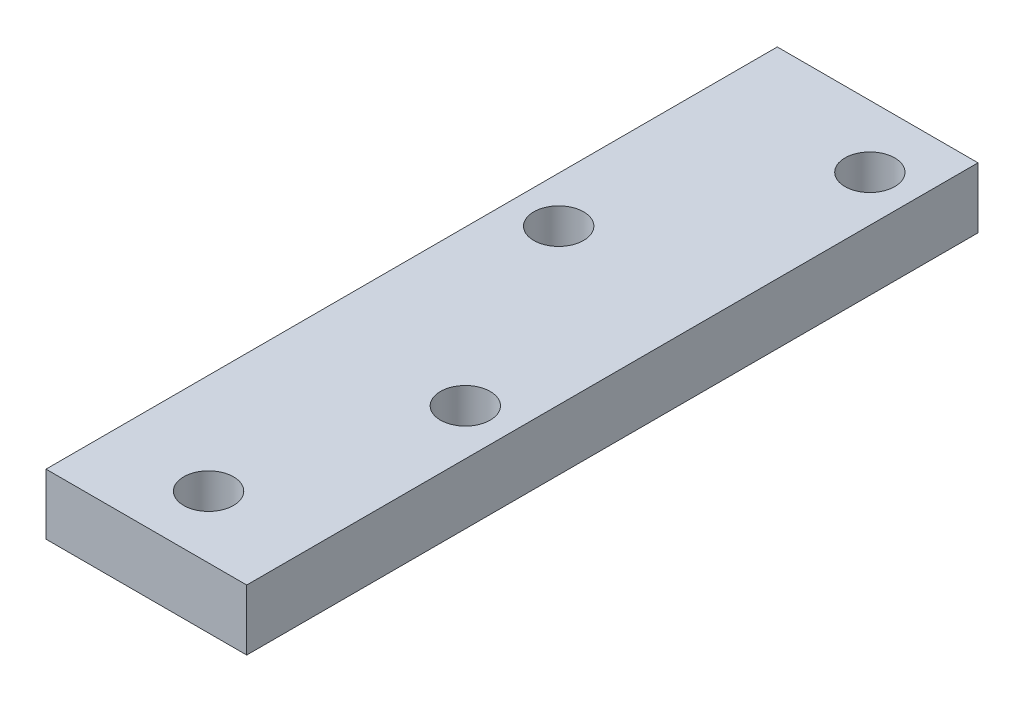
SolidWorks part; units mm, degrees
material "PLA"
ref_plane "前视基准面" through (0, 0, 0) normal (0, 0, 1) x (1, 0, 0)
ref_plane "上视基准面" through (0, 0, 0) normal (0, 1, 0) x (1, 0, 0)
ref_plane "右视基准面" through (0, 0, 0) normal (1, 0, 0) x (0, 0, -1)
sketch "草图1" plane through (0, 0, 0) normal (0, 0, 1) x (1, 0, 0)
  line L0 (0, 3) -> (0, -3)
  line L1 (7.5, -3) -> (0, -3)
  line L2 (7.5, -3) -> (7.5, 3)
  line L3 (7.5, 3) -> (0, 3)
  line L4 (-7.5, -3) -> (-7.5, 3) construction
  line L5 (7.5, -3) -> (-7.5, 3) construction
  line L6 (7.5, 3) -> (-7.5, -3) construction
  point P0 (0, 0)
  dimension "D1" = 15
  dimension "D2" = 6
extrude "凸台-拉伸1" add sketch "草图1" along normal blind 2
sketch "草图2" plane through (0, 0, 2) normal (0, 0, 1) x (1, 0, 0)
  line L1 (6.45, -1.95) -> (-6.45, -1.95)
  line L2 (6.45, -1.95) -> (6.45, 1.95)
  line L3 (6.45, 1.95) -> (-6.45, 1.95)
  line L4 (-6.45, -1.95) -> (-6.45, 1.95)
  line L5 (6.45, -1.95) -> (-6.45, 1.95) construction
  line L6 (6.45, 1.95) -> (-6.45, -1.95) construction
  point P0 (0, 0)
  dimension "D1" = 12.9
  dimension "D2" = 3.9
extrude "凸台-拉伸2" add sketch "草图2" along normal blind 52
sketch "草图3" plane through (0, -1.95, 0) normal (0, -1, 0) x (1, 0, 0)
  line L0 (3.5, 2) -> (3.5, 37) construction
  line L1 (0, 2) -> (6.45, 2) construction
  line L2 (7.5, 24.6481) -> (7.5, 6.8705) construction
  line L3 (-7.5, 24.6481) -> (-7.5, 6.3884) construction
  line L4 (0, 2) -> (7.5, 2) construction
  circle A0 centre (3.5, 37) radius 1.6
  circle A1 centre (3.5, 11) radius 1.6
  circle A2 centre (-3.5, 24) radius 1.6
  circle A3 centre (0, 50) radius 1.6
  dimension "D1" = 3.2
  dimension "D2" = 7.5
  dimension "D3" = 7.5
  dimension "D4" = 4
  dimension "D5" = 8
  dimension "D6" = 9
  dimension "D7" = 26
  dimension "D8" = 13
  dimension "D9" = 13
  dimension "D10" = 3.5
extrude "切除-拉伸1" cut sketch "草图3" against normal blind 356
sketch "草图4" plane through (0, 0, 2) normal (0, 0, 1) x (1, 0, 0)
  line L0 (0, 1.95) -> (7.5, 1.95)
  line L1 (7.5, -3) -> (7.5, 3) construction
  line L2 (7.5, 1.95) -> (7.5, 3)
  line L3 (7.5, 3) -> (0, 3)
  line L4 (0, 3) -> (0, 1.95)
extrude "切除-拉伸2" cut sketch "草图4" against normal blind 10
sketch "草图5" plane through (0, 1.95, 0) normal (0, 1, 0) x (1, 0, 0)
  line L1 (-11.1428, 16.1475) -> (11.1428, 16.1475)
  line L2 (-11.1428, 16.1475) -> (-11.1428, -7)
  line L3 (-11.1428, -7) -> (11.1428, -7)
  line L4 (11.1428, 16.1475) -> (11.1428, -7)
  line L5 (-11.1428, 16.1475) -> (11.1428, -7) construction
  line L6 (-11.1428, -7) -> (11.1428, 16.1475) construction
  point P0 (0, 4.5737)
  dimension "D1" = 7
extrude "切除-拉伸3" cut sketch "草图5" against normal blind 10
